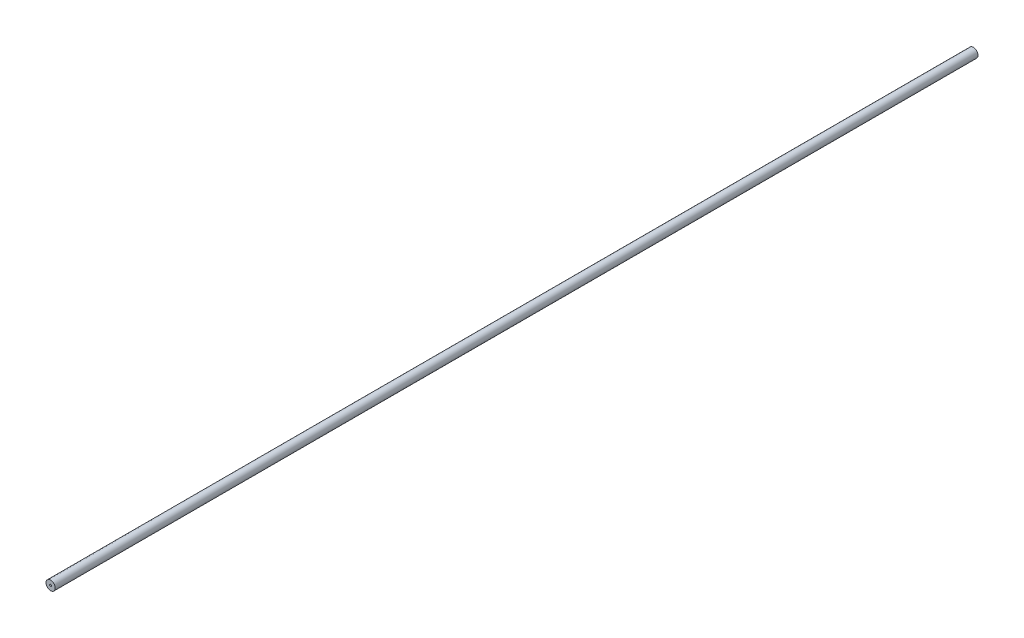
SolidWorks part; units mm, degrees
material "Zoltek Panex 33"
ref_plane "Front Plane" through (0, 0, 0) normal (0, 0, 1) x (1, 0, 0)
ref_plane "Top Plane" through (0, 0, 0) normal (0, 1, 0) x (1, 0, 0)
ref_plane "Right Plane" through (0, 0, 0) normal (1, 0, 0) x (0, 0, -1)
sketch "草圖1" plane through (0, 0, 0) normal (0, 0, 1) x (1, 0, 0)
  circle A0 centre (0, 0) radius 2.5
  dimension "D1" = 5
extrude "伸長-薄件2" add sketch "草圖1" along normal blind 500 thin thin type one direction reverse wall 2
